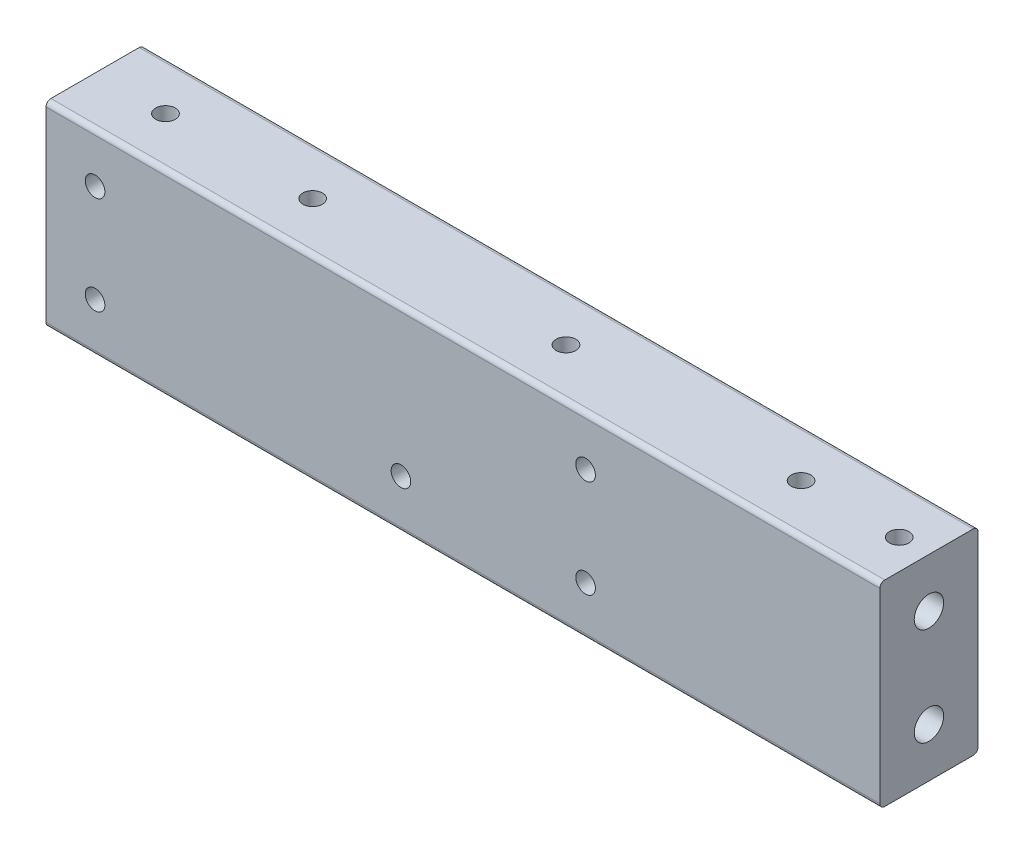
SolidWorks part; units mm, degrees
ref_plane "前视基准面" through (0, 0, 0) normal (0, 0, 1) x (1, 0, 0)
ref_plane "上视基准面" through (0, 0, 0) normal (0, 1, 0) x (1, 0, 0)
ref_plane "右视基准面" through (0, 0, 0) normal (1, 0, 0) x (0, 0, -1)
sketch "草图1" plane through (0, 0, 0) normal (0, 0, 1) x (1, 0, 0)
  line L1 (0, 0) -> (170, 0)
  line L2 (0, 0) -> (0, 40)
  line L3 (0, 40) -> (170, 40)
  line L4 (170, 0) -> (170, 40)
  dimension "D1" = 170
  dimension "D2" = 40
extrude "凸台-拉伸1" add sketch "草图1" along normal blind 20
fillet "圆角1" radius 1 4 edges at (85, 0, 0) (85, 40, 0) (85, 0, 20) (85, 40, 20)
sketch "草图2" plane through (0, 0, 0) normal (-1, 0, 0) x (0, 0, 1)
  line L0 (19, 40) -> (1, 40) construction
  line L1 (19, 0) -> (1, 0) construction
  line L2 (0, 39) -> (0, 1) construction
  circle A0 centre (10, 30) radius 3
  circle A1 centre (10, 10) radius 3
  dimension "D5" = 6
  dimension "D1" = 10
  dimension "D2" = 10
  dimension "D3" = 10
  dimension "D4" = 10
extrude "切除-拉伸1" cut sketch "草图2" against normal through all
sketch "草图3" plane through (0, 0, 20) normal (0, 0, 1) x (1, 0, 0)
  line L0 (0, 39) -> (0, 1) construction
  line L1 (0, 40) -> (170, 40) construction
  line L2 (170, 0) -> (0, 0) construction
  circle A0 centre (10, 30) radius 2
  circle A1 centre (10, 10) radius 2
  circle A2 centre (110, 30) radius 2
  circle A3 centre (110, 10) radius 2
  dimension "D5" = 4
  dimension "D1" = 10
  dimension "D2" = 10
  dimension "D3" = 10
  dimension "D4" = 100
extrude "切除-拉伸2" cut sketch "草图3" against normal blind 20
sketch "草图4" plane through (0, 0, 20) normal (0, 0, 1) x (1, 0, 0)
  circle A0 centre (72.3553, 10) radius 2
  dimension "D1" = 4
extrude "切除-拉伸3" cut sketch "草图4" against normal blind 20
sketch "草图5" plane through (0, 40, 0) normal (0, 1, 0) x (1, 0, 0)
  line L0 (170, -19) -> (170, -1) construction
  line L1 (0, 0) -> (170, 0) construction
  circle A0 centre (96, -10) radius 2
  circle A1 centre (143.9281, -10) radius 2
  circle A2 centre (163.9322, -10) radius 2
  circle A3 centre (14.3553, -10) radius 2
  circle A4 centre (44.3553, -10) radius 2
  dimension "D1" = 4
  dimension "D2" = 6.0678
  dimension "D3" = 20.004
  dimension "D4" = 47.9281
  dimension "D5" = 10
extrude "切除-拉伸4" cut sketch "草图5" against normal blind 40
